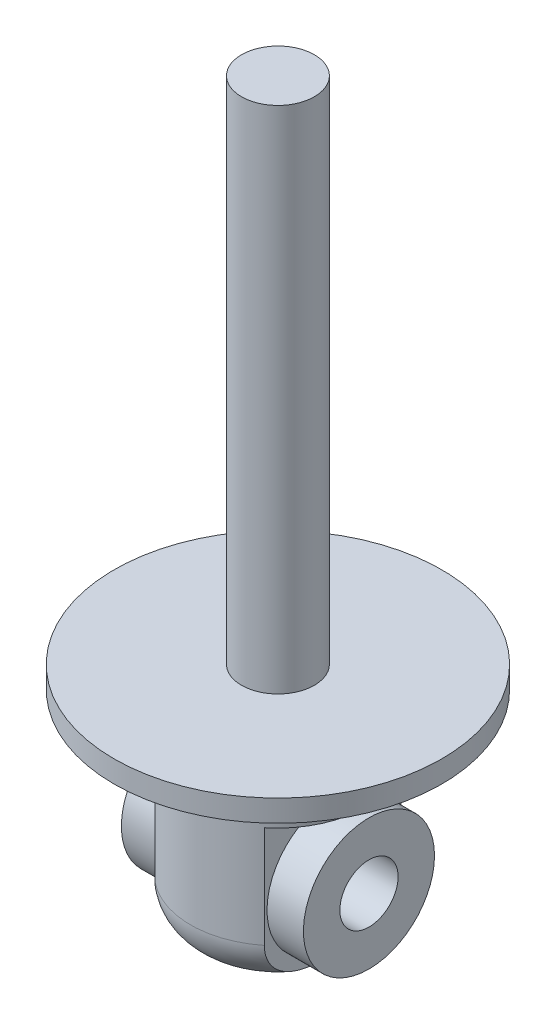
SolidWorks part; units mm, degrees
ref_plane "Front Plane" through (0, 0, 0) normal (0, 0, 1) x (1, 0, 0)
ref_plane "Top Plane" through (0, 0, 0) normal (0, 1, 0) x (1, 0, 0)
ref_plane "Right Plane" through (0, 0, 0) normal (1, 0, 0) x (0, 0, -1)
sketch "Sketch1" plane through (0, 0, 0) normal (0, 1, 0) x (1, 0, 0)
  circle A0 centre (0, 0) radius 22.5
  dimension "D1" = 45
extrude "Boss-Extrude1" add sketch "Sketch1" along normal blind 3
sketch "Sketch2" plane through (0, 3, 0) normal (0, 1, 0) x (1, 0, 0)
  circle A0 centre (0, 0) radius 5
  dimension "D1" = 10
extrude "Boss-Extrude2" add sketch "Sketch2" along normal blind 70
sketch "Sketch3" plane through (0, 0, 0) normal (0, -1, 0) x (1, 0, 0)
  circle A0 centre (0, 0) radius 12
  dimension "D1" = 24
extrude "Boss-Extrude3" add sketch "Sketch3" along normal blind 28
fillet "Fillet1" radius 6 1 edges at (0, -28, -12)
sketch "Sketch4" plane through (0, 0, 0) normal (0, 0, 1) x (1, 0, 0)
  line L0 (0, 0) -> (0, -28) construction
  line L1 (-6, -28) -> (6, -28) construction
  line L2 (-29.3629, -28) -> (-7.5, -28)
  line L3 (29.3629, -28) -> (29.3629, -8)
  line L4 (29.3629, -8) -> (7.5, -8)
  line L5 (7.5, -8) -> (7.5, -28)
  line L6 (-7.5, -8) -> (-7.5, -28)
  line L7 (-29.3629, -8) -> (-7.5, -8)
  line L8 (-29.3629, -28) -> (-29.3629, -8)
  line L9 (7.5, -28) -> (29.3629, -28)
  dimension "D1" = 15
  dimension "D2" = 20
  dimension "D3" = 21.8629
extrude "Cut-Extrude1" cut sketch "Sketch4" against normal through all both and the other way through all
sketch "Sketch5" plane through (7.5, 0, 0) normal (1, 0, 0) x (0, 0, -1)
  line L0 (0, 0) -> (0, -28) construction
  line L1 (-6, -28) -> (6, -28) construction
  circle A0 centre (0, -18) radius 4
  dimension "D1" = 8
  dimension "D2" = 10
extrude "Cut-Extrude3" cut sketch "Sketch5" against normal through all
sketch "Sketch7" plane through (0, 0, 0) normal (1, 0, 0) x (0, 0, -1)
  circle A0 centre (0, -18) radius 9
  circle A1 centre (0, -18) radius 4 construction
  circle A2 centre (0, -18) radius 4
  dimension "D1" = 18
extrude "Boss-Extrude4" add sketch "Sketch7" along normal mid plane 25
